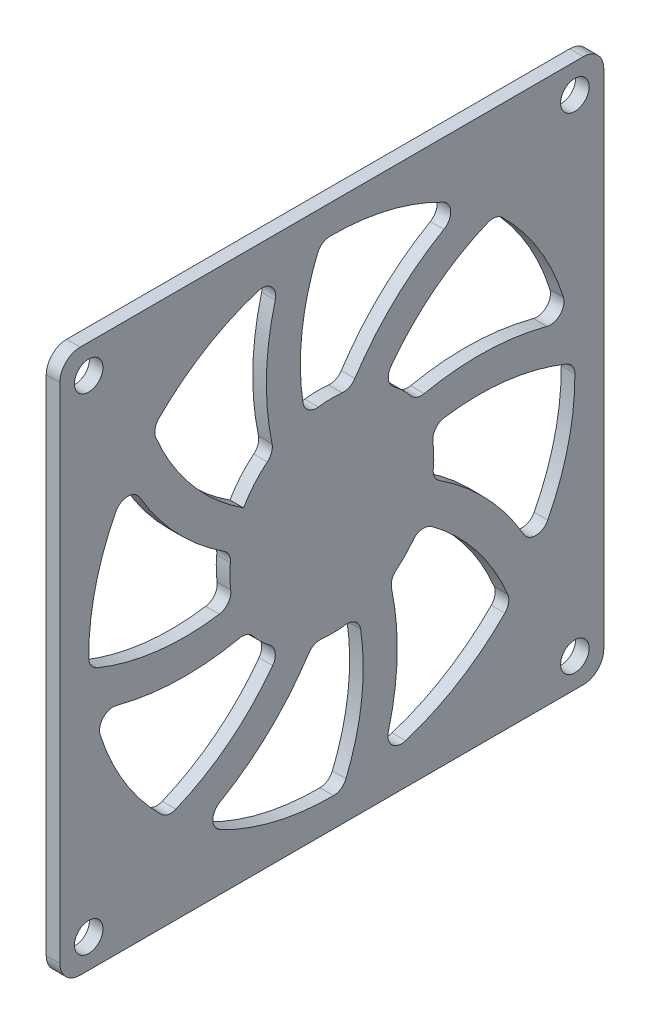
SolidWorks part; units mm, degrees
material "5052-H34"
ref_plane "正面" through (0, 0, 0) normal (0, 0, 1) x (1, 0, 0)
ref_plane "平面" through (0, 0, 0) normal (0, 1, 0) x (1, 0, 0)
ref_plane "右側面" through (0, 0, 0) normal (1, 0, 0) x (0, 0, -1)
sketch "ｽｹｯﾁ1" plane through (0, 0, 0) normal (1, 0, 0) x (0, 0, -1)
  line L1 (-40, 40) -> (40, 40)
  line L2 (-40, 40) -> (-40, -40)
  line L3 (-40, -40) -> (40, -40)
  line L4 (40, 40) -> (40, -40)
  line L5 (-40, 40) -> (40, -40) construction
  line L6 (-40, -40) -> (40, 40) construction
  line L7 (-35.75, 35.75) -> (35.75, 35.75) construction
  line L8 (-35.75, 35.75) -> (-35.75, -35.75) construction
  line L9 (-35.75, -35.75) -> (35.75, -35.75) construction
  line L10 (35.75, 35.75) -> (35.75, -35.75) construction
  line L11 (-35.75, 35.75) -> (35.75, -35.75) construction
  line L12 (-35.75, -35.75) -> (35.75, 35.75) construction
  circle A0 centre (35.75, 35.75) radius 2.1
  circle A1 centre (35.75, -35.75) radius 2.1
  circle A2 centre (-35.75, -35.75) radius 2.1
  circle A3 centre (-35.75, 35.75) radius 2.1
  point P0 (0, 0)
  point P6 (0, 0)
  dimension "D3" = 4.2
  dimension "D1" = 80
  dimension "D2" = 71.5
  dimension "D4" = 4
extrude "ﾎﾞｽ - 押し出し1" add sketch "ｽｹｯﾁ1" along normal blind 2
fillet "ﾌｨﾚｯﾄ1" radius 3 4 edges at (1, -40, -40) (1, -40, 40) (1, 40, -40) (1, 40, 40)
sketch "ｽｹｯﾁ5" plane through (2, 0, 0) normal (1, 0, 0) x (0, 0, -1)
  line L0 (36, 36) -> (-36, 36)
  line L1 (-20, 17.5) -> (20, 17.5) construction
  line L2 (-20, 17.5) -> (-20, -17.5) construction
  line L3 (-20, -17.5) -> (20, -17.5) construction
  line L4 (20, 17.5) -> (20, -17.5) construction
  line L5 (-20, 17.5) -> (20, -17.5) construction
  line L6 (-20, -17.5) -> (20, 17.5) construction
  line L7 (-36, 36) -> (-36, -36)
  line L8 (-36, -36) -> (36, -36)
  line L9 (36, -36) -> (36, 36)
  line L10 (-37, -40) -> (37, -40)
  line L11 (40, -37) -> (40, 37)
  line L12 (37, 40) -> (-37, 40)
  line L13 (-40, 37) -> (-40, -37)
  line L14 (-37, -40) -> (37, -40)
  line L15 (40, -37) -> (40, 37)
  line L16 (37, 40) -> (-37, 40)
  line L17 (-40, 37) -> (-40, -37)
  line L18 (0, 0) -> (0, 35.75) construction
  arc A0 (-36, 36) -> (-36, 36) centre (-36, 36) ccw
  arc A1 (-36, -36) -> (-36, -36) centre (-36, -36) ccw
  arc A2 (36, -36) -> (36, -36) centre (36, -36) ccw
  arc A3 (36, 36) -> (36, 36) centre (36, 36) ccw
  arc A4 (37, -40) -> (40, -37) centre (37, -37) ccw
  arc A5 (40, 37) -> (37, 40) centre (37, 37) ccw
  arc A6 (-37, 40) -> (-40, 37) centre (-37, 37) ccw
  arc A7 (-40, -37) -> (-37, -40) centre (-37, -37) ccw
  arc A8 (37, -40) -> (40, -37) centre (37, -37) ccw
  arc A9 (40, 37) -> (37, 40) centre (37, 37) ccw
  arc A10 (-37, 40) -> (-40, 37) centre (-37, 37) ccw
  arc A11 (-40, -37) -> (-37, -40) centre (-37, -37) ccw
  circle A13 centre (0, 0) radius 35.75
  circle A14 centre (0, 0) radius 15
  arc A15 (0, 0) -> (31, -36) centre (-5.4032, -36) cw construction
  arc A16 (-0.3711, -2.4723) -> (28.5, -36) centre (-5.4032, -36) cw
  arc A17 (0.3711, 2.4723) -> (33.5, -36) centre (-5.4032, -36) cw
  arc A18 (2.0106, 1.4858) -> (-1.7678, -49.1439) centre (-29.2765, -21.6352) cw
  arc A19 (-2.0106, -1.4858) -> (-5.3033, -45.6084) centre (-29.2765, -21.6352) cw
  arc A20 (2.4723, -0.3711) -> (-36, -33.5) centre (-36, 5.4032) cw
  arc A21 (-2.4723, 0.3711) -> (-36, -28.5) centre (-36, 5.4032) cw
  arc A22 (1.4858, -2.0106) -> (-49.1439, 1.7678) centre (-21.6352, 29.2765) cw
  arc A23 (-1.4858, 2.0106) -> (-45.6084, 5.3033) centre (-21.6352, 29.2765) cw
  arc A24 (-0.3711, -2.4723) -> (-33.5, 36) centre (5.4032, 36) cw
  arc A25 (0.3711, 2.4723) -> (-28.5, 36) centre (5.4032, 36) cw
  arc A26 (-2.0106, -1.4858) -> (1.7678, 49.1439) centre (29.2765, 21.6352) cw
  arc A27 (2.0106, 1.4858) -> (5.3033, 45.6084) centre (29.2765, 21.6352) cw
  arc A28 (-2.4723, 0.3711) -> (36, 33.5) centre (36, -5.4032) cw
  arc A29 (2.4723, -0.3711) -> (36, 28.5) centre (36, -5.4032) cw
  arc A30 (-1.4858, 2.0106) -> (49.1439, -1.7678) centre (21.6352, -29.2765) cw
  arc A31 (1.4858, -2.0106) -> (45.6084, -5.3033) centre (21.6352, -29.2765) cw
  point P0 (0, 0)
  dimension "D5" = 71.5
  dimension "D6" = 30
  dimension "D7" = 5
  dimension "D1" = 35
  dimension "D2" = 40
  dimension "D3" = 0
  dimension "D4" = 4
  dimension "D8" = 2.5
  dimension "D9" = 2.5
  dimension "D10" = 8
extrude "ｶｯﾄ - 押し出し2" cut sketch "ｽｹｯﾁ5" against normal through all contours A14 A28 A13 L0 A27 | L4 A30 L9 A13 A29 L1 | A31 A14 L4 A17 A13 L9 | A14 A18 L8 A13 A16 L4 L3 | A14 A20 A13 L8 A19 | L2 A22 L7 A13 A21 L3 | L2 A24 A13 L7 A23 A14 | A14 A26 L0 A13 A25 L2 L1
fillet "ﾌｨﾚｯﾄ2" radius 2 31 edges at (1, -12.3565, -8.504) (1, -7.5146, -12.9819) (1, -35.7158, -1.5645) (1, -14.4933, -3.8659) (1, -8.504, 12.3565) (1, -14.7506, 2.7241) (1, 19.6214, 29.8842) (1, -26.3611, 24.1486) (1, -1.5645, 35.7158) (1, -35.0057, -7.2569) (1, -29.8842, 19.6214) (1, -7.2569, 35.0057) (1, 24.1486, 26.3611) (1, -24.1486, -26.3611) (1, -12.9819, 7.5146) (1, -3.8659, 14.4933) (1, 2.7241, 14.7506) (1, 12.3565, 8.504) (1, 35.0057, 7.2569) (1, 14.4933, 3.8659) (1, 12.9819, -7.5146) (1, 1.5645, -35.7158) (1, 3.8659, -14.4933) (1, -19.6214, -29.8842) (1, -2.7241, -14.7506) (1, 8.504, -12.3565) (1, 14.7506, -2.7241) (1, 7.2569, -35.0057) (1, 29.8842, -19.6214) (1, 35.7158, 1.5645) (1, 26.3611, -24.1486)
